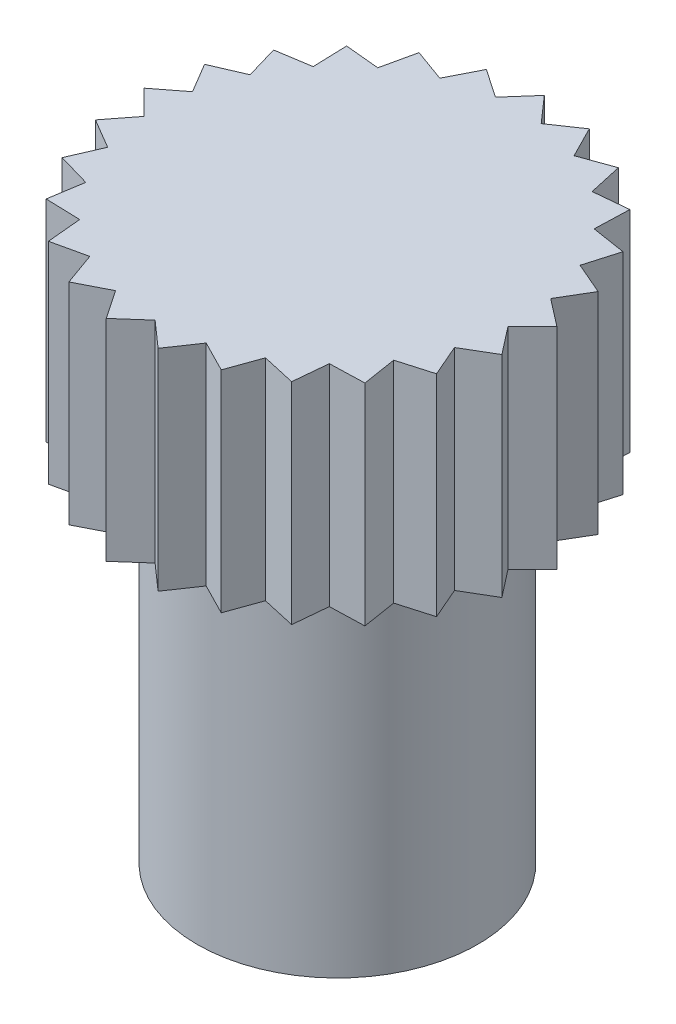
SolidWorks part; units mm, degrees
ref_plane "Front Plane" through (0, 0, 0) normal (0, 0, 1) x (1, 0, 0)
ref_plane "Top Plane" through (0, 0, 0) normal (0, 1, 0) x (1, 0, 0)
ref_plane "Right Plane" through (0, 0, 0) normal (1, 0, 0) x (0, 0, -1)
sketch "Sketch1" plane through (0, 0, 0) normal (0, 1, 0) x (1, 0, 0)
  circle A0 centre (0, 0) radius 2
extrude "Boss-Extrude1" add sketch "Sketch1" along normal blind 5.01
sketch "Sketch4" plane through (0, 5.01, 0) normal (0, 1, 0) x (1, 0, 0)
  line L0 (0, 0) -> (0, 2.95) construction
  line L1 (0, 0) -> (0.3697, 2.9267) construction
  line L2 (0, 0) -> (0.7336, 2.8573) construction
  line L3 (0, 0) -> (1.086, 2.7428) construction
  line L4 (0, 0) -> (1.4212, 2.5851) construction
  line L5 (0, 0) -> (1.734, 2.3866) construction
  line L6 (0, 0) -> (2.0194, 2.1505) construction
  line L7 (0, 0) -> (2.273, 1.8804) construction
  line L8 (0, 0) -> (2.4908, 1.5807) construction
  line L9 (0, 0) -> (2.6692, 1.256) construction
  line L10 (0, 0) -> (2.8056, 0.9116) construction
  line L11 (0, 0) -> (2.8977, 0.5528) construction
  line L12 (0, 0) -> (2.9442, 0.1852) construction
  line L13 (0, 0) -> (2.9442, -0.1852) construction
  line L14 (0, 0) -> (2.8977, -0.5528) construction
  line L15 (0, 0) -> (2.8056, -0.9116) construction
  line L16 (0, 0) -> (2.6692, -1.256) construction
  line L17 (0, 0) -> (2.4908, -1.5807) construction
  line L18 (0, 0) -> (2.273, -1.8804) construction
  line L19 (0, 0) -> (2.0194, -2.1505) construction
  line L20 (0, 0) -> (1.734, -2.3866) construction
  line L21 (0, 0) -> (1.4212, -2.5851) construction
  line L22 (0, 0) -> (1.086, -2.7428) construction
  line L23 (0, 0) -> (0.7336, -2.8573) construction
  line L24 (0, 0) -> (0.3697, -2.9267) construction
  line L25 (0, 0) -> (0, -2.95) construction
  line L26 (0, 0) -> (-0.3697, -2.9267) construction
  line L27 (0, 0) -> (-0.7336, -2.8573) construction
  line L28 (0, 0) -> (-1.086, -2.7428) construction
  line L29 (0, 0) -> (-1.4212, -2.5851) construction
  line L30 (0, 0) -> (-1.734, -2.3866) construction
  line L31 (0, 0) -> (-2.0194, -2.1505) construction
  line L32 (0, 0) -> (-2.273, -1.8804) construction
  line L33 (0, 0) -> (-2.4908, -1.5807) construction
  line L34 (0, 0) -> (-2.6692, -1.256) construction
  line L35 (0, 0) -> (-2.8056, -0.9116) construction
  line L36 (0, 0) -> (-2.8977, -0.5528) construction
  line L37 (0, 0) -> (-2.9442, -0.1852) construction
  line L38 (0, 0) -> (-2.9442, 0.1852) construction
  line L39 (0, 0) -> (-2.8977, 0.5528) construction
  line L40 (0, 0) -> (-2.8056, 0.9116) construction
  line L41 (0, 0) -> (-2.6692, 1.256) construction
  line L42 (0, 0) -> (-2.4908, 1.5807) construction
  line L43 (0, 0) -> (-2.273, 1.8804) construction
  line L44 (0, 0) -> (-2.0194, 2.1505) construction
  line L45 (0, 0) -> (-1.734, 2.3866) construction
  line L46 (0, 0) -> (-1.4212, 2.5851) construction
  line L47 (0, 0) -> (-1.086, 2.7428) construction
  line L48 (0, 0) -> (-0.7336, 2.8573) construction
  line L49 (0, 0) -> (-0.3697, 2.9267) construction
  line L50 (0, 2.95) -> (0.3259, 2.5795)
  line L51 (0.3259, 2.5795) -> (0.7336, 2.8573)
  line L52 (0.7336, 2.8573) -> (0.9571, 2.4174)
  line L53 (0.9571, 2.4174) -> (1.4212, 2.5851)
  line L54 (1.4212, 2.5851) -> (1.5282, 2.1034)
  line L55 (1.5282, 2.1034) -> (2.0194, 2.1505)
  line L56 (2.0194, 2.1505) -> (2.0033, 1.6573)
  line L57 (2.0033, 1.6573) -> (2.4908, 1.5807)
  line L58 (2.4908, 1.5807) -> (2.3526, 1.107)
  line L59 (2.3526, 1.107) -> (2.8056, 0.9116)
  line L60 (2.8056, 0.9116) -> (2.5539, 0.4872)
  line L61 (2.5539, 0.4872) -> (2.9442, 0.1852)
  line L62 (2.9442, 0.1852) -> (2.5949, -0.1633)
  line L63 (2.5949, -0.1633) -> (2.8977, -0.5528)
  line L64 (2.8977, -0.5528) -> (2.4727, -0.8034)
  line L65 (2.4727, -0.8034) -> (2.6692, -1.256)
  line L66 (2.6692, -1.256) -> (2.1953, -1.3931)
  line L67 (2.1953, -1.3931) -> (2.273, -1.8804)
  line L68 (2.273, -1.8804) -> (1.7798, -1.8953)
  line L69 (1.7798, -1.8953) -> (1.734, -2.3866)
  line L70 (1.734, -2.3866) -> (1.2526, -2.2784)
  line L71 (1.2526, -2.2784) -> (1.086, -2.7428)
  line L72 (1.086, -2.7428) -> (0.6466, -2.5183)
  line L73 (0.6466, -2.5183) -> (0.3697, -2.9267)
  line L74 (0.3697, -2.9267) -> (0, -2.6)
  line L75 (0, -2.6) -> (-0.3697, -2.9267)
  line L76 (-0.3697, -2.9267) -> (-0.6466, -2.5183)
  line L77 (-0.6466, -2.5183) -> (-1.086, -2.7428)
  line L78 (-1.086, -2.7428) -> (-1.2526, -2.2784)
  line L79 (-1.2526, -2.2784) -> (-1.734, -2.3866)
  line L80 (-1.734, -2.3866) -> (-1.7798, -1.8953)
  line L81 (-1.7798, -1.8953) -> (-2.273, -1.8804)
  line L82 (-2.273, -1.8804) -> (-2.1953, -1.3931)
  line L83 (-2.1953, -1.3931) -> (-2.6692, -1.256)
  line L84 (-2.6692, -1.256) -> (-2.4727, -0.8034)
  line L85 (-2.4727, -0.8034) -> (-2.8977, -0.5528)
  line L86 (-2.8977, -0.5528) -> (-2.5949, -0.1633)
  line L87 (-2.5949, -0.1633) -> (-2.9442, 0.1852)
  line L88 (-2.9442, 0.1852) -> (-2.5539, 0.4872)
  line L89 (-2.5539, 0.4872) -> (-2.8056, 0.9116)
  line L90 (-2.8056, 0.9116) -> (-2.3526, 1.107)
  line L91 (-2.3526, 1.107) -> (-2.4908, 1.5807)
  line L92 (-2.4908, 1.5807) -> (-2.0033, 1.6573)
  line L93 (-2.0033, 1.6573) -> (-2.0194, 2.1505)
  line L94 (-2.0194, 2.1505) -> (-1.5282, 2.1034)
  line L95 (-1.5282, 2.1034) -> (-1.4212, 2.5851)
  line L96 (-1.4212, 2.5851) -> (-0.9571, 2.4174)
  line L97 (-0.9571, 2.4174) -> (-0.7336, 2.8573)
  line L98 (-0.7336, 2.8573) -> (-0.3259, 2.5795)
  line L99 (-0.3259, 2.5795) -> (0, 2.95)
  circle A0 centre (0, 0) radius 2.95 construction
  circle A1 centre (0, 0) radius 2.6 construction
  point P56 (0, 0)
  point P130 (0, 0)
  dimension "D1" = 25
  dimension "D2" = 50
extrude "Boss-Extrude2" add sketch "Sketch4" along normal blind 3 contours L99 L98 L97 L96 L95 L94 L93 L92 L91 L90 L89 L88 L87 L86 L85 L84 L83 L82 L81 L80 L79 L78 L77 L76 L75 L74 L73 L72 L71 L70 L69 L68 L67 L66 L65 L64 L63 L62 L61 L60 L59 L58 L57 L56 L55 L54 L53 L52 L51 L50
